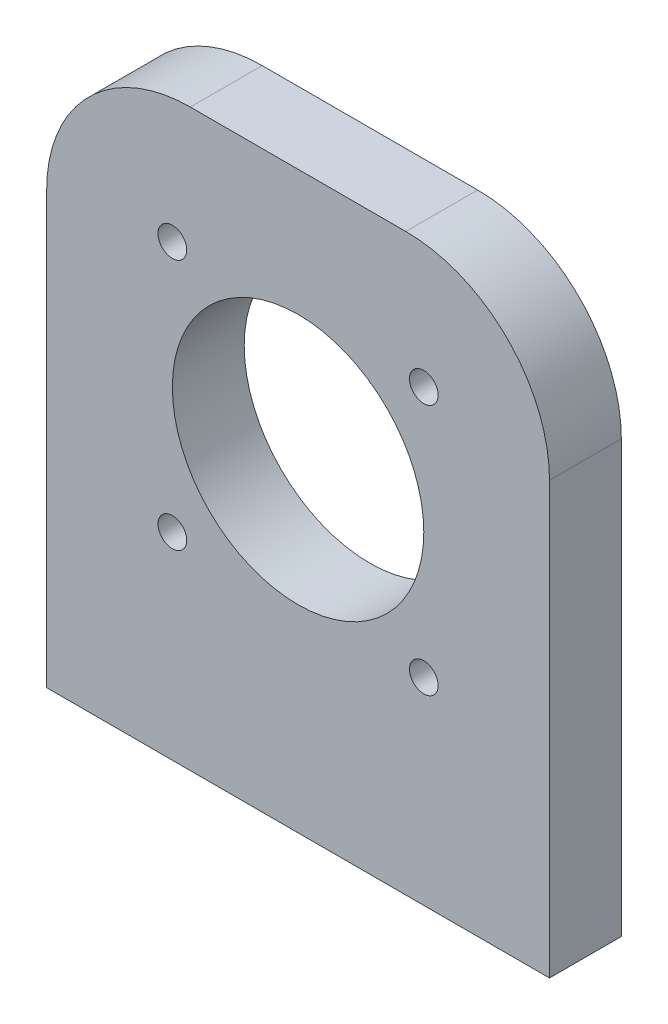
SolidWorks part; units mm, degrees
material "6061-T6 (SS)"
ref_plane "Front Plane" through (0, 0, 0) normal (0, 0, 1) x (1, 0, 0)
ref_plane "Top Plane" through (0, 0, 0) normal (0, 1, 0) x (1, 0, 0)
ref_plane "Right Plane" through (0, 0, 0) normal (1, 0, 0) x (0, 0, -1)
sketch "Sketch1" plane through (0, 0, 0) normal (0, 0, 1) x (1, 0, 0)
  line L0 (0, 0) -> (70, 0)
  line L1 (0, 0) -> (0, -80)
  line L2 (70, 0) -> (70, -80)
  line L3 (0, -80) -> (70, -80)
  line L4 (10, -80) -> (60, -80) construction
  line L5 (10, -80) -> (10, -110) construction
  line L6 (60, -80) -> (60, -110) construction
  line L7 (10, -110) -> (60, -110) construction
  circle A0 centre (35, -35) radius 17.5
  point P7 (35, -80)
  point P8 (35, 0)
  point P11 (35, -80)
  dimension "D3" = 35
  dimension "D1" = 70
  dimension "D2" = 80
  dimension "D4" = 35
  dimension "D5" = 50
  dimension "D6" = 30
extrude "Boss-Extrude1" add sketch "Sketch1" along normal blind 10 contours L5 L7 L6 L3 | A0
fillet "Fillet1" radius 20 2 edges at (70, 0, 5) (0, 0, 5)
sketch "Sketch2" plane through (0, 0, 10) normal (0, 0, 1) x (1, 0, 0)
  line L0 (17.5, -52.5) -> (52.5, -52.5) construction
  line L1 (17.5, -52.5) -> (17.5, -17.5) construction
  line L2 (17.5, -17.5) -> (52.5, -17.5) construction
  line L3 (52.5, -52.5) -> (52.5, -17.5) construction
  line L4 (17.5, -52.5) -> (52.5, -17.5) construction
  line L5 (17.5, -17.5) -> (52.5, -52.5) construction
  circle A0 centre (17.5, -17.5) radius 2
  circle A1 centre (52.5, -17.5) radius 2
  circle A2 centre (52.5, -52.5) radius 2
  circle A3 centre (17.5, -52.5) radius 2
  circle A4 centre (35, -35) radius 17.5 construction
  point P0 (35, -35)
  dimension "D2" = 4
  dimension "D1" = 35
extrude "Cut-Extrude1" cut sketch "Sketch2" against normal blind 10
